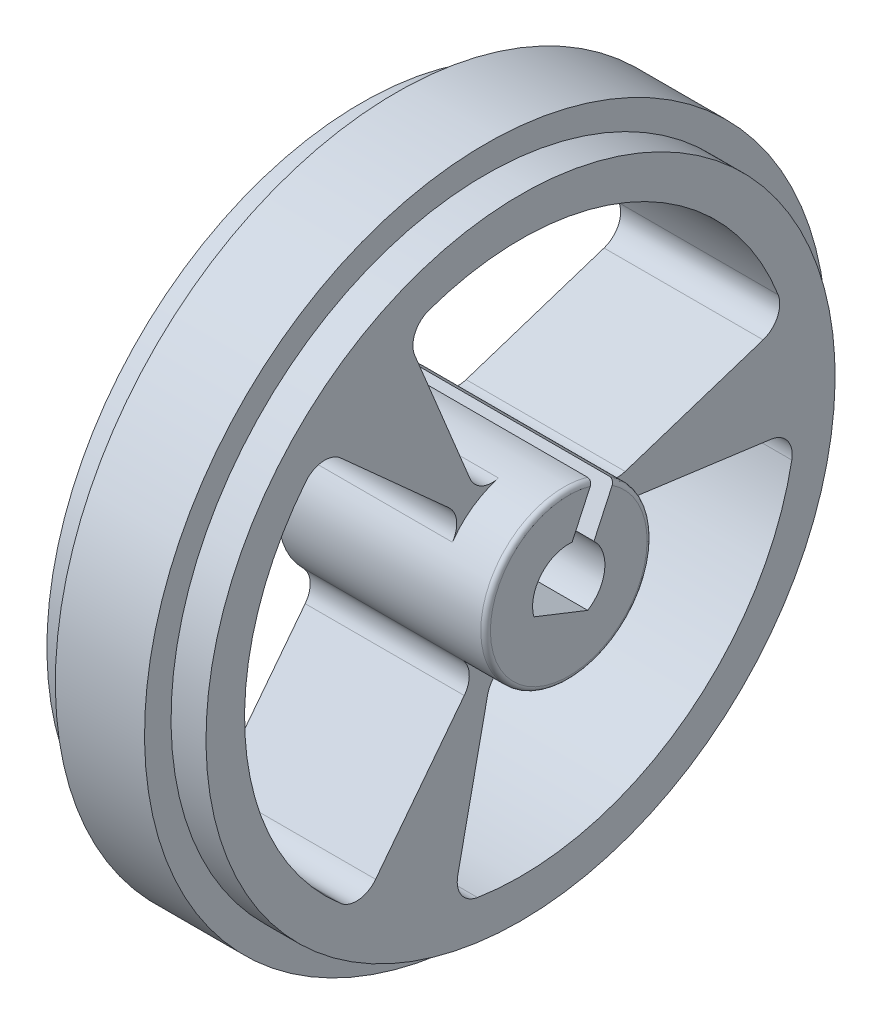
SolidWorks part; units mm, degrees
ref_plane "Přední rovina" through (0, 0, 0) normal (0, 0, 1) x (1, 0, 0)
ref_plane "Horní rovina" through (0, 0, 0) normal (0, 1, 0) x (1, 0, 0)
ref_plane "Pravá rovina" through (0, 0, 0) normal (1, 0, 0) x (0, 0, -1)
sketch "Skica1" plane through (0, 0, 0) normal (0, 0, 1) x (1, 0, 0)
  line L0 (0, 14.15) -> (0, 0) construction
  line L1 (1.85, 14.15) -> (-1.85, 14.15)
  line L2 (-1.85, 14.15) -> (-1.85, 13.05)
  line L3 (1.85, 14.15) -> (1.85, 13.05)
  line L4 (-1.85, 13.05) -> (-3.3, 13.05)
  line L5 (1.85, 13.05) -> (3.3, 13.05)
  line L6 (-3.3, 13.05) -> (-3.3, 0)
  line L7 (3.3, 13.05) -> (3.3, 0)
  line L8 (-3.3, 0) -> (3.3, 0)
  dimension "D1" = 13.05
  dimension "D2" = 1.1
  dimension "D3" = 6.6
  dimension "D4" = 3.7
  dimension "D5" = 14.15
revolve "Rotovat1" add sketch "Skica1" angle 360 about L8
sketch "Skica2" plane through (3.3, 0, 0) normal (1, 0, 0) x (0, 0, -1)
  line L0 (3.3932, 0.6234) -> (11.0188, 3.1125)
  line L1 (3.45, 0) -> (11.3999, -1.0702)
  line L2 (-1.1567, -3.2503) -> (-2.8139, -11.0988)
  line L3 (-1.725, -2.9878) -> (-6.6267, -9.3375)
  line L4 (-2.2365, 2.6269) -> (-8.2049, 7.9863)
  line L5 (-1.725, 2.9878) -> (-4.7732, 10.4077)
  line L6 (-2.2365, 2.6269) -> (-1.725, 2.9878) construction
  line L7 (-1.725, 2.9878) -> (-1.9807, 2.8073) construction
  line L8 (-1.9807, 2.8073) -> (-7.3219, 10.3773) construction
  circle A0 centre (0, 0) radius 11.45
  circle A1 centre (0, 0) radius 13.05 construction
  circle A2 centre (0, 0) radius 3.45
  point P16 (0, 0)
  point P21 (0, 0)
  point P25 (0, 0)
  dimension "D1" = 1.6
  dimension "D2" = 6.9
  dimension "D4" = 2.1
  dimension "D5" = 0.626
  dimension "D6" = 2.1
  dimension "D3" = 3
extrude "Odebrat vysunutím1" cut sketch "Skica2" against normal blind 10 contours A2 L0 A0 L5 | A2 L4 A0 L3 | A2 L2 A0 L1
fillet "Zaoblit1" radius 1 1 edges at (0, 7.9863, 8.2049)
fillet "Zaoblit2" radius 1 5 edges at (0, -9.3375, 6.6267) (0, -11.0988, 2.8139) (0, -1.0702, -11.3999) (0, 3.1125, -11.0188) (0, 10.4077, 4.7732)
fillet "Zaoblit4" radius 1 6 edges at (0, -3.2503, 1.1567) (0, 0, -3.45) (0, 0.6234, -3.3932) (0, 2.9878, 1.725) (0, -2.9878, 1.725) (0, 2.6269, 2.2365)
sketch "Skica3" plane through (3.3, 0, 0) normal (1, 0, 0) x (0, 0, -1)
  line L0 (0, 0) -> (1.4468, 3.132) construction
  line L1 (0.1392, 1.4935) -> (0.9776, 3.3086)
  line L2 (0.7857, -1.2778) -> (-1.4467, -0.3965)
  line L3 (1.047, 1.0742) -> (1.8855, 2.8892)
  circle A0 centre (0, 0) radius 1.5
  arc A2 (3.1256, 1.4604) -> (-0.9142, 3.3267) centre (0, 0) ccw construction
  dimension "D1" = 3
  dimension "D2" = 0.5
  dimension "D3" = 0.5
  dimension "D4" = 0.6
extrude "Odebrat vysunutím2" cut sketch "Skica3" against normal blind 10
sketch "Skica5" plane through (3.3, 0, 0) normal (1, 0, 0) x (0, 0, -1)
  line L0 (0.9776, 3.3086) -> (0.1392, 1.4935)
  line L1 (1.8855, 2.8892) -> (1.047, 1.0742)
  line L2 (0.7857, -1.2778) -> (-1.4467, -0.3965) construction
  line L3 (-1.4467, -0.3965) -> (0.7857, -1.2778)
  arc A0 (0.9776, 3.3086) -> (1.8855, 2.8892) centre (0, 0) ccw
  arc A1 (-1.4467, -0.3965) -> (0.1392, 1.4935) centre (0, 0) cw
  arc A2 (0.1392, 1.4935) -> (-1.4467, -0.3965) centre (0, 0) ccw construction
  arc A3 (0.7857, -1.2778) -> (1.047, 1.0742) centre (0, 0) ccw
  arc A4 (0.7857, -1.2778) -> (1.047, 1.0742) centre (0, 0) ccw construction
extrude "Přidat vysunutím1" add sketch "Skica5" along normal blind 2
fillet "Zaoblit5" radius 0.2 1 edges at (5.3, -3.132, 1.4468)
